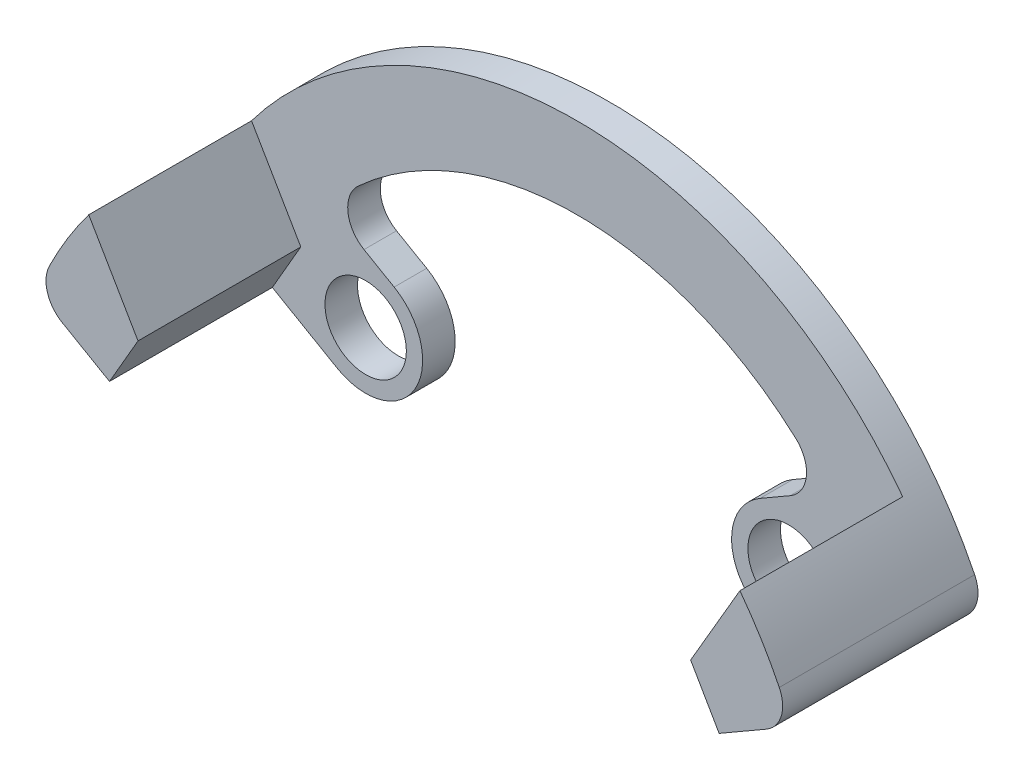
SolidWorks part; units mm, degrees
material "6061-T6 (SS)"
ref_plane "Front Plane" through (0, 0, 0) normal (0, 0, 1) x (1, 0, 0)
ref_plane "Top Plane" through (0, 0, 0) normal (0, 1, 0) x (1, 0, 0)
ref_plane "Right Plane" through (0, 0, 0) normal (1, 0, 0) x (0, 0, -1)
sketch "Sketch1" plane through (0, 0, 0) normal (0, 0, 1) x (1, 0, 0)
  line L0 (0, 7.5) -> (0, -7.5) construction
  line L1 (-7.5, 0) -> (7.5, 0) construction
  line L4 (10.8129, 4.2226) -> (7.37, 2.2348)
  line L5 (5.62, 5.2659) -> (6.5462, 5.8006)
  line L6 (-10.8129, 4.2226) -> (-7.37, 2.2348)
  line L7 (-5.62, 5.2659) -> (-6.5462, 5.8006)
  circle A0 centre (0, 0) radius 7.5 construction
  arc A1 (6.718, 7.4074) -> (-6.718, 7.4074) centre (0, 0) ccw
  arc A2 (11.2097, 5.5311) -> (-11.2097, 5.5311) centre (0, 0) ccw
  circle A3 centre (-6.495, 3.7503) radius 1.25
  circle A4 centre (6.495, 3.7503) radius 1.25
  arc A5 (-7.37, 2.2348) -> (-5.62, 5.2659) centre (-6.495, 3.7503) ccw
  arc A6 (5.62, 5.2659) -> (7.37, 2.2348) centre (6.495, 3.7503) ccw
  arc A8 (-6.5462, 5.8006) -> (-6.718, 7.4074) centre (-6.0462, 6.6666) cw
  arc A9 (6.5462, 5.8006) -> (6.718, 7.4074) centre (6.0462, 6.6666) ccw
  arc A10 (10.8129, 4.2226) -> (11.2097, 5.5311) centre (10.3129, 5.0886) ccw
  arc A11 (-10.8129, 4.2226) -> (-11.2097, 5.5311) centre (-10.3129, 5.0886) cw
  point P23 (-7.6514, 6.4387)
  point P26 (7.6514, 6.4387)
  point P29 (11.5936, 4.6733)
  point P32 (-11.5936, 4.6733)
  dimension "D1" = 15
  dimension "D2" = 2.5
  dimension "D3" = 10
  dimension "D5" = 2.5
  dimension "D7" = 3.5
  dimension "D8" = 1
  dimension "D4" = 60
  dimension "D6" = 12.99
extrude "Boss-Extrude1" add sketch "Sketch1" against normal blind 1
sketch "Sketch2" plane through (0, 0, 0) normal (0, 0, 1) x (1, 0, 0)
  line L0 (0, 0) -> (0, 10) construction
  line L1 (9.3619, 3.3848) -> (8.4869, 4.9003)
  line L2 (7.37, 2.2348) -> (10.8129, 4.2226) construction
  line L3 (8.4869, 4.9003) -> (10, 7.5)
  line L4 (9.3619, 3.3848) -> (10.8129, 4.2226)
  line L5 (6.495, 3.7503) -> (8.4869, 4.9003) construction
  line L6 (-9.3619, 3.3848) -> (-10.8129, 4.2226)
  line L7 (-8.4869, 4.9003) -> (-10, 7.5)
  line L8 (-9.3619, 3.3848) -> (-8.4869, 4.9003)
  arc A0 (6.718, 7.4074) -> (-6.718, 7.4074) centre (0, 0) ccw construction
  arc A1 (11.2097, 5.5311) -> (-11.2097, 5.5311) centre (0, 0) ccw construction
  arc A2 (10.8129, 4.2226) -> (11.2097, 5.5311) centre (10.3129, 5.0886) ccw construction
  arc A3 (10.8129, 4.2226) -> (11.2097, 5.5311) centre (10.3129, 5.0886) ccw
  arc A4 (11.2097, 5.5311) -> (10, 7.5) centre (0, 0) ccw
  arc A5 (-11.2097, 5.5311) -> (-10, 7.5) centre (0, 0) cw
  arc A6 (-10.8129, 4.2226) -> (-11.2097, 5.5311) centre (-10.3129, 5.0886) cw
  dimension "D1" = 2.3
  dimension "D2" = 10
extrude "Boss-Extrude2" add sketch "Sketch2" along normal blind 5
